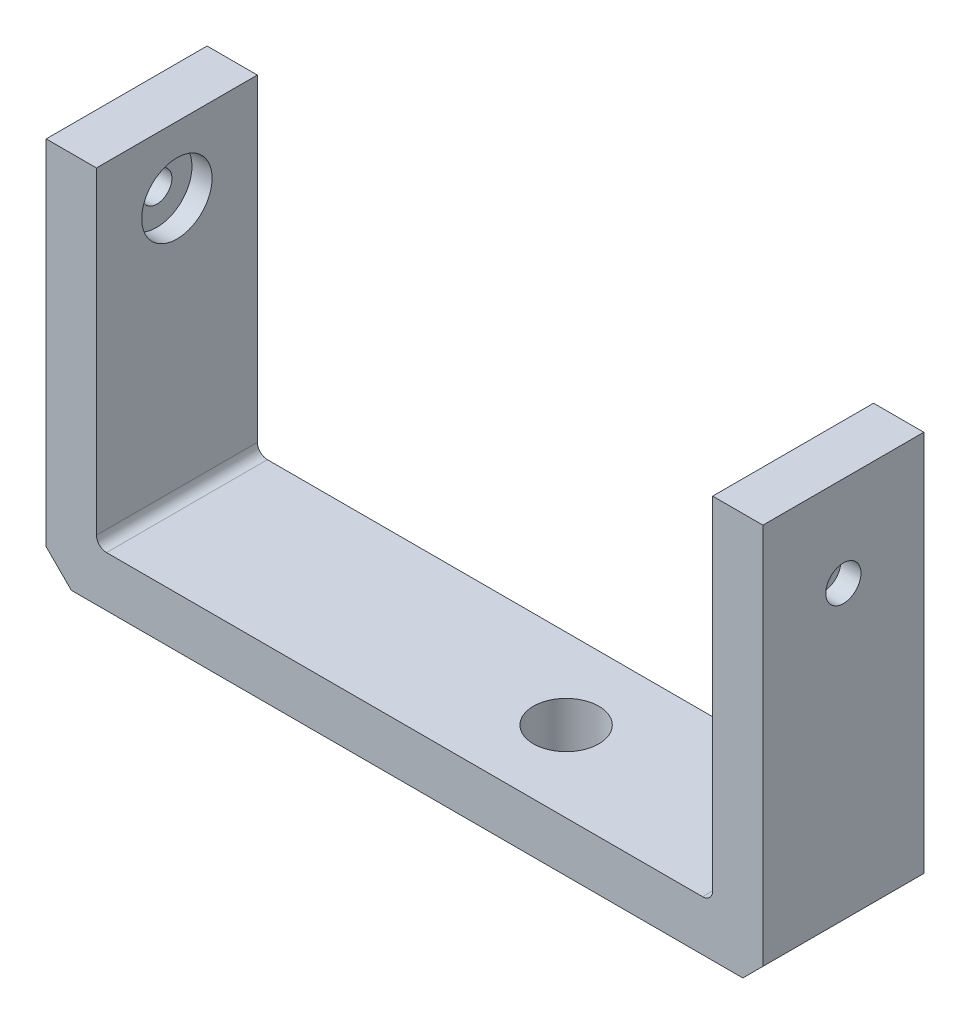
SolidWorks part; units mm, degrees
ref_plane "Front Plane" through (0, 0, 0) normal (0, 0, 1) x (1, 0, 0)
ref_plane "Top Plane" through (0, 0, 0) normal (0, 1, 0) x (1, 0, 0)
ref_plane "Right Plane" through (0, 0, 0) normal (1, 0, 0) x (0, 0, -1)
sketch "Sketch1" plane through (0, 0, 0) normal (0, 0, 1) x (1, 0, 0)
  line L1 (11.3793, 29.5172) -> (16.3793, 29.5172)
  line L2 (-17.8966, -5.4828) -> (-17.8966, -10.4828)
  line L3 (-17.8966, -10.4828) -> (16.3793, -10.4828)
  line L4 (16.3793, 29.5172) -> (16.3793, -10.4828)
  line L7 (-18.6207, -5.4828) -> (11.3793, -5.4828)
  line L8 (11.3793, 29.5172) -> (11.3793, -5.4828)
  dimension "D1" = 30
  dimension "D2" = 35
  dimension "D3" = 5
  dimension "D4" = 5
extrude "Boss-Extrude1" add sketch "Sketch1" along normal blind 16 contours L1 L8 L7 L2 L3 L4
sketch "Sketch2" plane through (0, -5.4828, 0) normal (0, 1, 0) x (1, 0, 0)
  circle A0 centre (-11.1922, -8) radius 3.25
  dimension "D1" = 6.5
extrude "Cut-Extrude1" cut sketch "Sketch2" against normal blind 20
fillet "Fillet1" radius 1 1 edges at (11.3793, -5.4828, 8)
chamfer "Chamfer1" distance 2 angle 45 1 edges at (16.3793, -10.4828, 8)
sketch "Sketch3" plane through (11.3793, 0, 0) normal (-1, 0, 0) x (0, 0, 1)
  line L0 (0, -4.4828) -> (16, -4.4828) construction
  circle A0 centre (8, 20.5172) radius 1.75
  dimension "D1" = 25
  dimension "D2" = 3.5
extrude "Cut-Extrude2" cut sketch "Sketch3" against normal blind 20
sketch "Sketch4" plane through (11.3793, 0, 0) normal (-1, 0, 0) x (0, 0, 1)
  circle A0 centre (8, 20.5172) radius 3
  dimension "D1" = 6
extrude "Cut-Extrude3" cut sketch "Sketch4" against normal blind 3
sketch "Sketch5" plane through (14.3793, 0, 0) normal (-1, 0, 0) x (0, 0, 1)
  circle A0 centre (8, 20.5172) radius 3
extrude "Boss-Extrude2" add sketch "Sketch5" along normal blind 2
sketch "Sketch6" plane through (12.3793, 0, 0) normal (-1, 0, 0) x (0, 0, 1)
  circle A0 centre (8, 20.5172) radius 1
  dimension "D1" = 2
extrude "Cut-Extrude4" cut sketch "Sketch6" against normal blind 2
sketch "Sketch7" plane through (-17.8966, 0, 0) normal (-1, 0, 0) x (0, 0, 1)
  line L1 (0, -5.4828) -> (16, -5.4828)
  line L2 (0, -5.4828) -> (0, -10.4828)
  line L3 (0, -10.4828) -> (16, -10.4828)
  line L4 (16, -5.4828) -> (16, -10.4828)
extrude "Boss-Extrude3" add sketch "Sketch7" along normal blind 37
sketch "Sketch8" plane through (0, -5.4828, 0) normal (0, 1, 0) x (1, 0, 0)
  line L0 (-54.8966, 0) -> (10.3793, 0) construction
  line L1 (-54.8966, -16) -> (-49.8966, -16)
  line L2 (-54.8966, -16) -> (-54.8966, 0)
  line L3 (-54.8966, 0) -> (-49.8966, 0)
  line L4 (-49.8966, -16) -> (-49.8966, 0)
  dimension "D1" = 5
extrude "Boss-Extrude4" add sketch "Sketch8" along normal blind 37
sketch "Sketch9" plane through (14.3793, 0, 0) normal (1, 0, 0) x (0, 0, -1)
  circle A0 centre (-8, 20.5172) radius 1
extrude "Cut-Extrude5" cut sketch "Sketch9" against normal blind 87
sketch "Sketch10" plane through (-49.8966, 0, 0) normal (1, 0, 0) x (0, 0, -1)
  circle A0 centre (-8, 20.5172) radius 3.5
  dimension "D1" = 7
extrude "Cut-Extrude6" cut sketch "Sketch10" against normal blind 2
sketch "Sketch11" plane through (-51.8966, 0, 0) normal (1, 0, 0) x (0, 0, -1)
  circle A0 centre (-8, 20.5172) radius 1.5
  dimension "D1" = 3
extrude "Cut-Extrude7" cut sketch "Sketch11" against normal blind 12
chamfer "Chamfer2" distance 2.5 angle 45 1 edges at (-54.8966, -10.4828, 8)
fillet "Fillet2" radius 1 1 edges at (-49.8966, -5.4828, 8)
sketch "Sketch12" plane through (-49.8966, 0, 0) normal (1, 0, 0) x (0, 0, -1)
  line L0 (0, 31.5172) -> (0, -4.4828) construction
  line L1 (-16, 31.5172) -> (0, 31.5172)
  line L2 (-16, 31.5172) -> (-16, 27.1409)
  line L3 (-16, 27.1409) -> (0, 27.1409)
  line L4 (0, 31.5172) -> (0, 27.1409)
extrude "Cut-Extrude8" cut sketch "Sketch12" against normal blind 12
